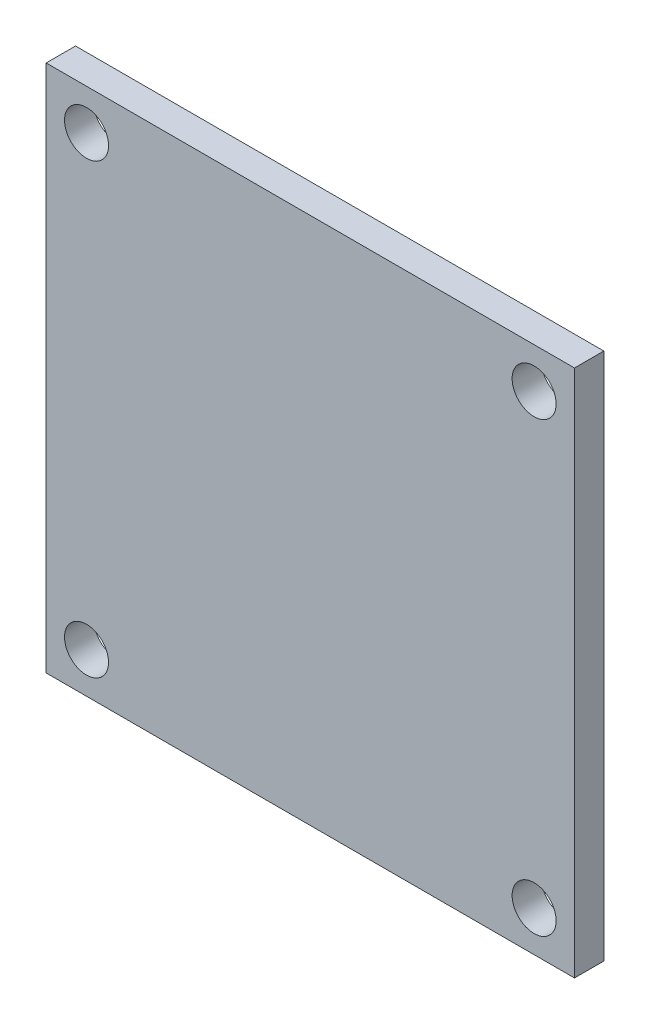
SolidWorks part; units mm, degrees
ref_plane "Plan de face" through (0, 0, 0) normal (0, 0, 1) x (1, 0, 0)
ref_plane "Plan de dessus" through (0, 0, 0) normal (0, 1, 0) x (1, 0, 0)
ref_plane "Plan de droite" through (0, 0, 0) normal (1, 0, 0) x (0, 0, -1)
sketch "Esquisse1" plane through (0, 0, 0) normal (0, 0, 1) x (1, 0, 0)
  line L0 (-18, 18) -> (18, -18) construction
  line L1 (-18, 18) -> (18, 18)
  line L2 (-18, 18) -> (-18, -18)
  line L3 (-18, -18) -> (18, -18)
  line L4 (18, 18) -> (18, -18)
  line L5 (0, 15.25) -> (0, -15.25) construction
  line L6 (-15.25, 15.25) -> (15.25, 15.25) construction
  line L7 (-15.25, 15.25) -> (-15.25, -15.25) construction
  line L8 (-15.25, -15.25) -> (15.25, -15.25) construction
  line L9 (15.25, 15.25) -> (15.25, -15.25) construction
  circle A0 centre (15.25, 15.25) radius 1.5
  circle A1 centre (-15.25, 15.25) radius 1.5
  circle A2 centre (-15.25, -15.25) radius 1.5
  circle A3 centre (15.25, -15.25) radius 1.5
  dimension "D4" = 3
  dimension "D5" = 3
  dimension "D6" = 3
  dimension "D7" = 3
  dimension "D1" = 36
  dimension "D2" = 36
  dimension "D3" = 30.5
extrude "Boss.-Extru.1" add sketch "Esquisse1" along normal blind 2
